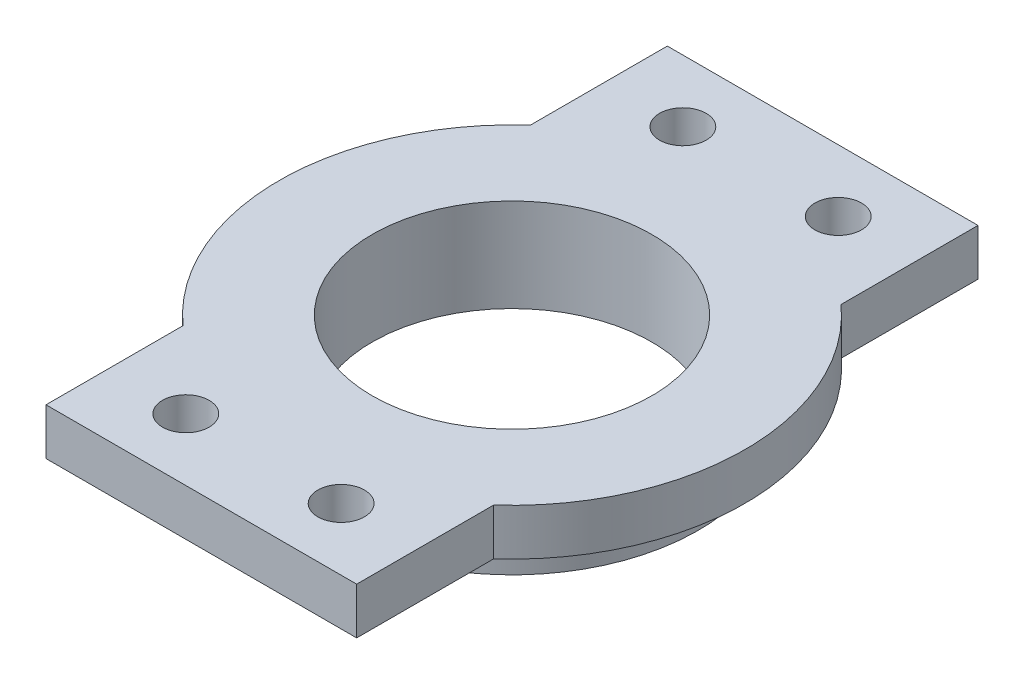
SolidWorks part; units mm, degrees
ref_plane "前视基准面" through (0, 0, 0) normal (0, 0, 1) x (1, 0, 0)
ref_plane "上视基准面" through (0, 0, 0) normal (0, 1, 0) x (1, 0, 0)
ref_plane "右视基准面" through (0, 0, 0) normal (1, 0, 0) x (0, 0, -1)
other "Configuration Table"
sketch "草图1" plane through (0, 0, 0) normal (0, 1, 0) x (1, 0, 0)
  circle A0 centre (0, 0) radius 9
  circle A1 centre (0, 0) radius 12
  dimension "D1" = 18
  dimension "D2" = 24
extrude "凸台-拉伸1" add sketch "草图1" along normal blind 3
sketch "草图2" plane through (0, 3, 0) normal (0, 1, 0) x (1, 0, 0)
  line L0 (-10, -11.1803) -> (-10, -20)
  line L1 (-10, 20) -> (10, 20)
  line L2 (-10, 20) -> (-10, 11.1803)
  line L3 (-10, -20) -> (10, -20)
  line L4 (10, 20) -> (10, 11.1803)
  line L5 (-10, 20) -> (10, -20) construction
  line L6 (-10, -20) -> (10, 20) construction
  line L7 (5, -16) -> (-5, -16) construction
  line L8 (5, -16) -> (5, 16) construction
  line L9 (5, 16) -> (-5, 16) construction
  line L10 (-5, -16) -> (-5, 16) construction
  line L11 (5, -16) -> (-5, 16) construction
  line L12 (5, 16) -> (-5, -16) construction
  line L13 (10, -11.1803) -> (10, -20)
  circle A2 centre (0, 0) radius 9 construction
  circle A3 centre (0, 0) radius 9
  circle A4 centre (-5, 16) radius 1.5
  circle A5 centre (5, 16) radius 1.5
  circle A6 centre (-5, -16) radius 1.5
  circle A7 centre (5, -16) radius 1.5
  arc A8 (-10, 11.1803) -> (-10, -11.1803) centre (0, 0) ccw
  arc A10 (10, -11.1803) -> (10, 11.1803) centre (0, 0) ccw
  dimension "D1" = 20
  dimension "D5" = 3
  dimension "D6" = 30
  dimension "D2" = 40
  dimension "D3" = 10
  dimension "D4" = 32
extrude "凸台-拉伸2" add sketch "草图2" along normal blind 3
